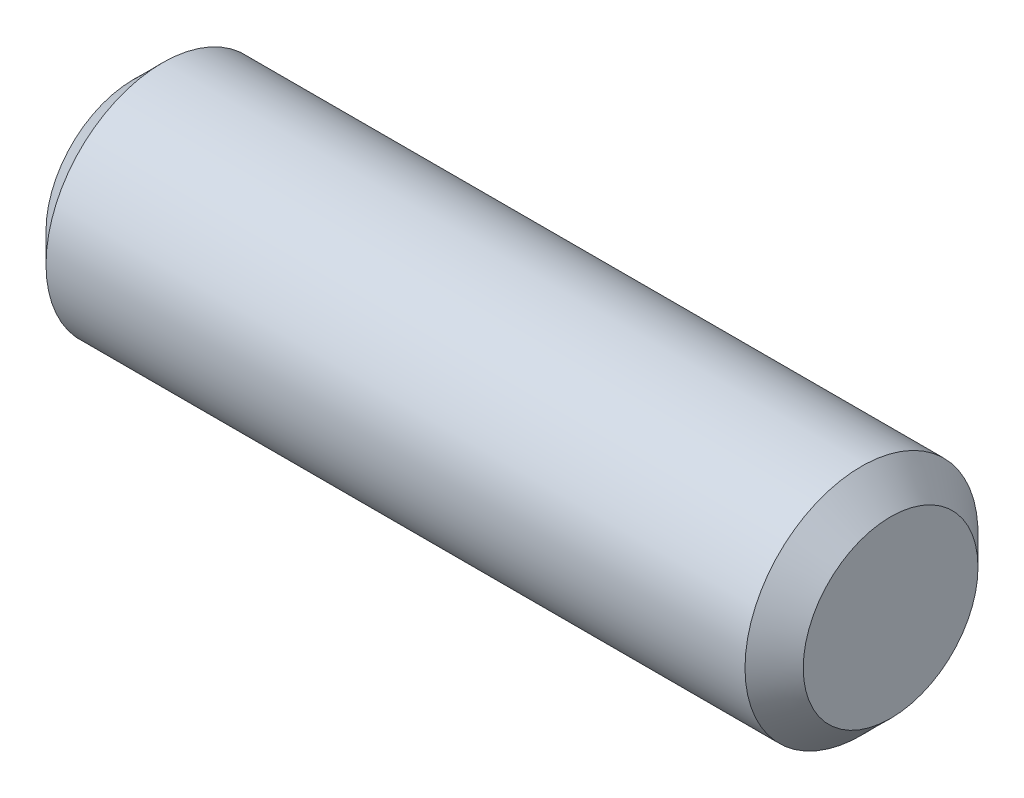
SolidWorks part; units mm, degrees
ref_plane "Front Plane" through (0, 0, 0) normal (0, 0, 1) x (1, 0, 0)
ref_plane "Top Plane" through (0, 0, 0) normal (0, 1, 0) x (1, 0, 0)
ref_plane "Right Plane" through (0, 0, 0) normal (1, 0, 0) x (0, 0, -1)
sketch "Sketch2" plane through (0, 0, 0) normal (1, 0, 0) x (0, 0, -1)
  circle A0 centre (0, 0) radius 2
extrude "Boss-Extrude1" add sketch "Sketch2" along normal blind 13
chamfer "Chamfer1" distance 0.5 angle 45 2 edges at (13, 0, -2) (0, 0, -2)
scale "Echelle1" scale about centroid uniform scaling yes scale factor 2
scale "Echelle2" scale about centroid uniform scaling yes scale factor 0.25
